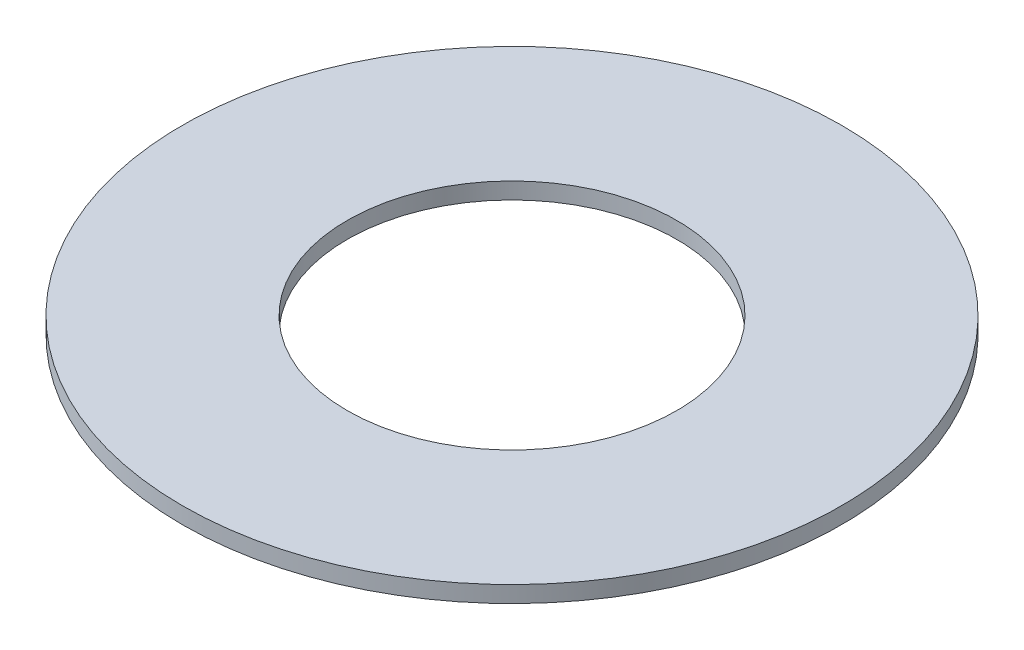
SolidWorks part; units mm, degrees
ref_plane "Front" through (0, 0, 0) normal (0, 0, 1) x (1, 0, 0)
ref_plane "Top" through (0, 0, 0) normal (0, 1, 0) x (1, 0, 0)
ref_plane "Right" through (0, 0, 0) normal (1, 0, 0) x (0, 0, -1)
sketch "草图1" plane through (0, 0, 0) normal (0, 1, 0) x (1, 0, 0)
  circle A0 centre (0, 0) radius 1
  circle A1 centre (0, 0) radius 2
extrude "凸台-拉伸1" add sketch "草图1" along normal blind 0.1
